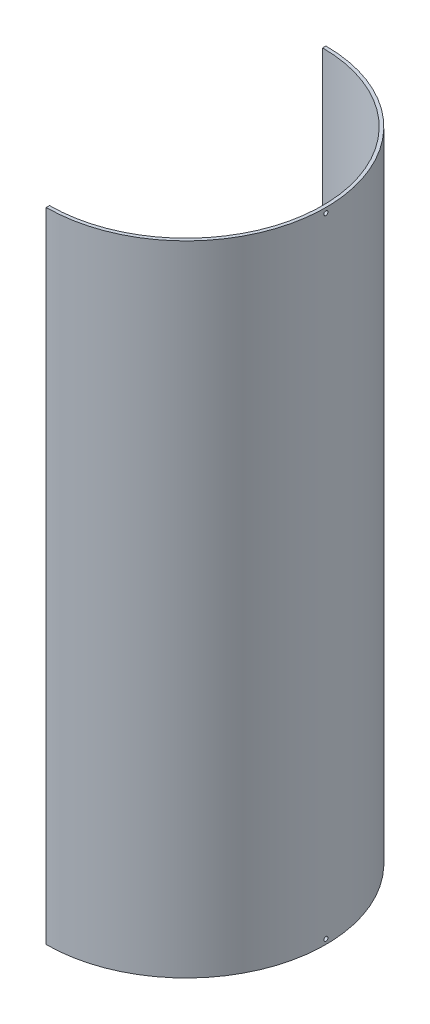
SolidWorks part; units mm, degrees
material "Glass"
ref_plane "Front Plane" through (0, 0, 0) normal (0, 0, 1) x (1, 0, 0)
ref_plane "Top Plane" through (0, 0, 0) normal (0, 1, 0) x (1, 0, 0)
ref_plane "Right Plane" through (0, 0, 0) normal (1, 0, 0) x (0, 0, -1)
sketch "Sketch1" plane through (0, 0, 0) normal (0, 1, 0) x (1, 0, 0)
  line L0 (0, 85) -> (0, 83)
  line L1 (0, -83) -> (0, -85)
  line L2 (0, 0) -> (0, 92.978) construction
  arc A0 (0, -85) -> (0, 85) centre (0, 0) ccw
  arc A1 (0, -83) -> (0, 83) centre (0, 0) ccw
  dimension "D1" = 85
  dimension "D2" = 83
extrude "Boss-Extrude1" add sketch "Sketch1" along normal blind 388
sketch "Sketch2" plane through (0, 0, 0) normal (1, 0, 0) x (0, 0, -1)
  line L0 (85, 388) -> (-85, 388) construction
  line L1 (-85, 0) -> (85, 0) construction
  circle A0 centre (0, 385) radius 1.25
  circle A1 centre (0, 3) radius 1.25
  dimension "D1" = 2.5
  dimension "D3" = 2.5
  dimension "D2" = 3
  dimension "D4" = 3
extrude "Cut-Extrude1" cut sketch "Sketch2" along normal blind 202
